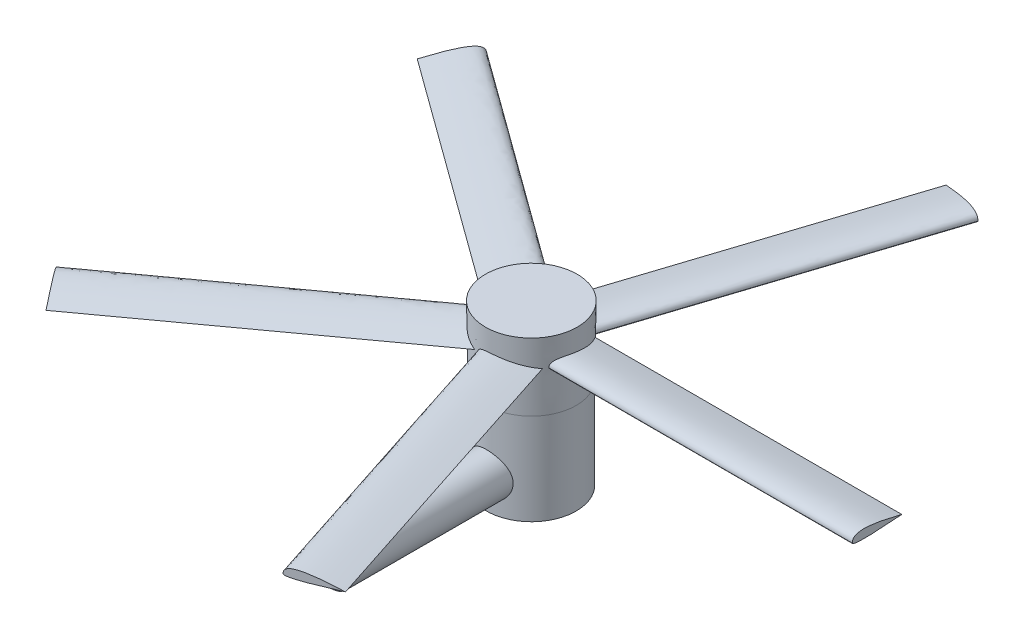
SolidWorks part; units mm, degrees
ref_plane "Front Plane" through (0, 0, 0) normal (0, 0, 1) x (1, 0, 0)
ref_plane "Top Plane" through (0, 0, 0) normal (0, 1, 0) x (1, 0, 0)
ref_plane "Right Plane" through (0, 0, 0) normal (1, 0, 0) x (0, 0, -1)
sketch "Sketch1" plane through (0, 0, 0) normal (0, 0, 1) x (1, 0, 0)
  line L0 (0, 223.5827) -> (0, 540.2222) construction
  line L5 (39.8608, 304.8) -> (0, 264.9392)
  line L6 (0, 223.5827) -> (0, 264.9392)
  line L7 (39.8608, 304.8) -> (39.8608, 223.5827)
  line L8 (39.8608, 223.5827) -> (0, 223.5827)
revolve "Revolve1" add sketch "Sketch1" angle 360 about L0
sketch "Sketch2" plane through (0, 0, 0) normal (1, 0, 0) x (0, 0, -1)
  line L0 (39.8608, 304.8) -> (40.7526, 365.5211)
  line L1 (40.7526, 365.5211) -> (0, 365.5211)
  line L2 (39.8608, 304.8) -> (0, 264.9392)
  line L3 (0, 264.9392) -> (39.8608, 304.8) construction
  line L4 (0, 365.5211) -> (0, 264.9392) construction
  line L5 (0, 365.5211) -> (0, 264.9392)
  line L6 (39.8608, 223.5827) -> (39.8608, 304.8) construction
revolve "Revolve2" add sketch "Sketch2" angle 360 about L4
sketch "Sketch3" plane through (0, 0, 0) normal (1, 0, 0) x (0, 0, -1)
  line L7 (24.2929, 341.3155) -> (-19.7529, 341.3155) construction
  line L8 (0, 406.1724) -> (0, 353.1218) construction
  line L9 (-19.7529, 341.3155) -> (-19.7529, 350.8622) construction
  line L10 (-19.7529, 350.8622) -> (0.4086, 347.398) construction
  line L11 (0.4086, 347.398) -> (24.2929, 341.3155) construction
  line L12 (-19.7529, 341.3155) -> (-19.7529, 337.7618) construction
  line L13 (-19.7529, 337.7618) -> (24.2929, 341.3155) construction
  line L14 (40.7526, 365.5211) -> (-40.7526, 365.5211) construction
  spline S2 degree 3 poles (-19.7529, 341.3155) (-19.7529, 350.8622) (0.4086, 347.398) (24.2929, 341.3155) knots 0 0 0 0 1 1 1 1
  spline S3 degree 2 poles (-19.7529, 341.3155) (-19.7529, 337.7618) (24.2929, 341.3155) knots 0 0 0 1 1 1
  point P16 (2.27, 341.3155)
extrude "Boss-Extrude1" add sketch "Sketch3" along normal blind 304.8
pattern_circular "CirPattern1" count 5 over 360 about axis through (0, 365.5211, 0) along (0, 1, 0) of "Boss-Extrude1"
sketch "Sketch4" plane through (0, 0, 0) normal (0, 0, 1) x (1, 0, 0)
  circle A0 centre (0, 251.9151) radius 18.94
extrude "Boss-Extrude2" add sketch "Sketch4" along normal blind 177.8 contours A0
